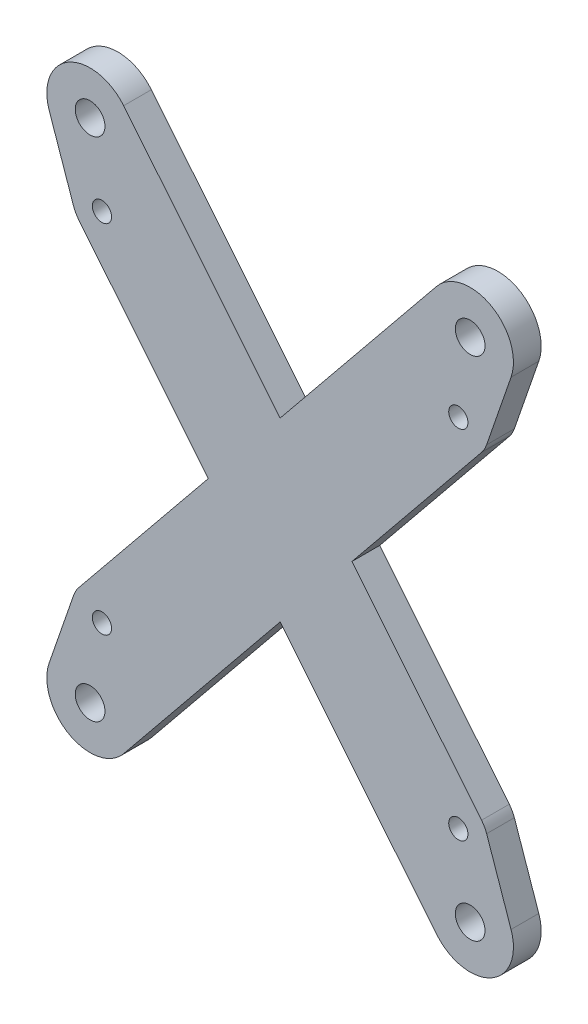
SolidWorks part; units mm, degrees
material "ABS PC"
ref_plane "Front Plane" through (0, 0, 0) normal (0, 0, 1) x (1, 0, 0)
ref_plane "Top Plane" through (0, 0, 0) normal (0, 1, 0) x (1, 0, 0)
ref_plane "Right Plane" through (0, 0, 0) normal (1, 0, 0) x (0, 0, -1)
sketch "Sketch1" plane through (0, 0, 0) normal (0, 0, 1) x (1, 0, 0)
  line L0 (-23.0598, 18.2358) -> (-8.2219, 0)
  line L1 (-21.7551, -28.9941) -> (21.7551, -28.9941) construction
  line L2 (-21.7551, -28.9941) -> (-21.7551, 28.9941) construction
  line L3 (-21.7551, 28.9941) -> (21.7551, 28.9941) construction
  line L4 (21.7551, -28.9941) -> (21.7551, 28.9941) construction
  line L5 (-21.7551, -28.9941) -> (21.7551, 28.9941) construction
  line L6 (-21.7551, 28.9941) -> (21.7551, -28.9941) construction
  line L7 (-20.4, -20.4) -> (20.4, -20.4) construction
  line L8 (-20.4, -20.4) -> (-20.4, 20.4) construction
  line L9 (-20.4, 20.4) -> (20.4, 20.4) construction
  line L10 (20.4, -20.4) -> (20.4, 20.4) construction
  line L11 (-20.4, -20.4) -> (20.4, 20.4) construction
  line L12 (-20.4, 20.4) -> (20.4, -20.4) construction
  line L13 (-26.4369, 27.3776) -> (-23.6412, 19.2809)
  line L14 (0, 52.5104) -> (0, -49.3971) construction
  line L15 (-17.9132, 32.1201) -> (0, 10.1047)
  line L16 (-50.5509, 0) -> (59.0035, 0) construction
  line L17 (26.4369, 27.3776) -> (23.6412, 19.2809)
  line L18 (23.0598, 18.2358) -> (8.2219, 0)
  line L19 (17.9132, 32.1201) -> (0, 10.1047)
  line L20 (26.4369, -27.3776) -> (23.6412, -19.2809)
  line L21 (23.0598, -18.2358) -> (8.2219, 0)
  line L22 (17.9132, -32.1201) -> (0, -10.1047)
  line L23 (-26.4369, -27.3776) -> (-23.6412, -19.2809)
  line L24 (-17.9132, -32.1201) -> (0, -10.1047)
  line L25 (-23.0598, -18.2358) -> (-8.2219, 0)
  circle A0 centre (21.7551, 28.9941) radius 1.7018
  circle A1 centre (-21.7551, 28.9941) radius 1.7018
  circle A2 centre (-21.7551, -28.9941) radius 1.7018
  circle A3 centre (21.7551, -28.9941) radius 1.7018
  circle A4 centre (20.4, 20.4) radius 1.1
  circle A5 centre (-20.4, 20.4) radius 1.1
  circle A6 centre (-20.4, -20.4) radius 1.1
  circle A7 centre (20.4, -20.4) radius 1.1
  arc A8 (-23.6412, 19.2809) -> (-23.0598, 18.2358) centre (-20.4, 20.4) ccw
  arc A9 (-17.9132, 32.1201) -> (-26.4369, 27.3776) centre (-21.7551, 28.9941) ccw
  arc A10 (23.0598, 18.2358) -> (23.6412, 19.2809) centre (20.4, 20.4) ccw
  arc A11 (26.4369, 27.3776) -> (17.9132, 32.1201) centre (21.7551, 28.9941) ccw
  arc A12 (17.9132, -32.1201) -> (26.4369, -27.3776) centre (21.7551, -28.9941) ccw
  arc A13 (23.6412, -19.2809) -> (23.0598, -18.2358) centre (20.4, -20.4) ccw
  arc A14 (-26.4369, -27.3776) -> (-17.9132, -32.1201) centre (-21.7551, -28.9941) ccw
  arc A15 (-23.0598, -18.2358) -> (-23.6412, -19.2809) centre (-20.4, -20.4) ccw
  circle A17 centre (0, 0) radius 6.35 construction
  circle A18 centre (-20.4, 20.4) radius 3.429 construction
  circle A19 centre (-21.7551, 28.9941) radius 4.953 construction
  circle A20 centre (21.7551, 28.9941) radius 4.953 construction
  circle A21 centre (20.4, 20.4) radius 3.429 construction
  circle A22 centre (21.7551, -28.9941) radius 4.953 construction
  circle A23 centre (20.4, -20.4) radius 3.429 construction
  circle A24 centre (-21.7551, -28.9941) radius 4.953 construction
  circle A25 centre (-20.4, -20.4) radius 3.429 construction
  point P0 (0, 0)
  point P10 (0, 0)
  dimension "D3" = 3.4036
  dimension "D5" = 2.2
  dimension "D6" = 40.8
  dimension "D7" = 6.858
  dimension "D8" = 9.906
  dimension "D1" = 43.5102
  dimension "D2" = 57.9882
  dimension "D4" = 40.8
extrude "Boss-Extrude1" add sketch "Sketch1" along normal blind 3.175
